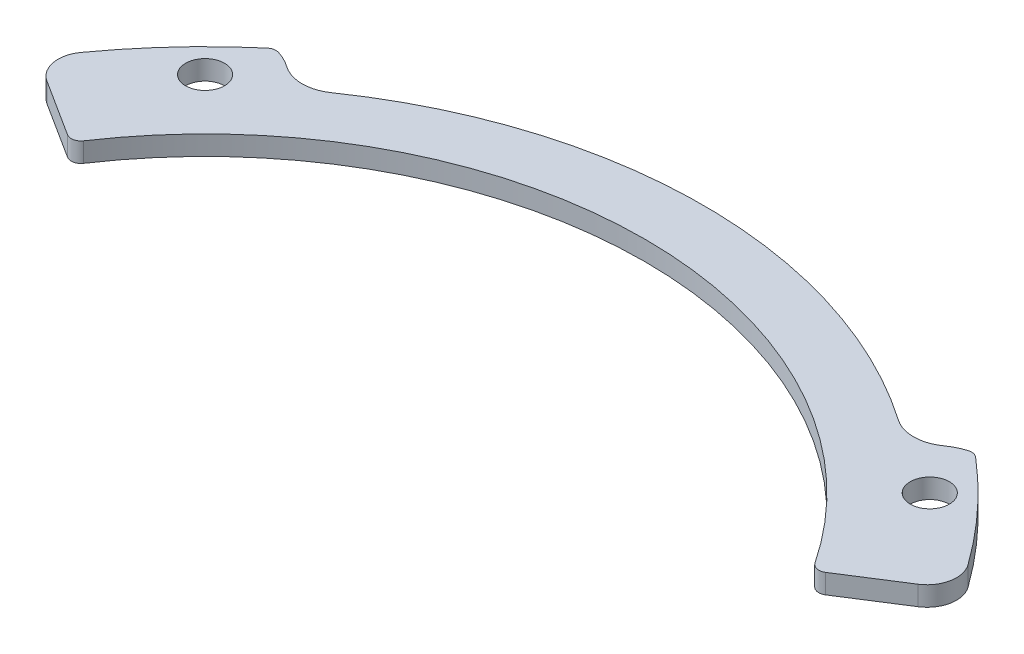
SolidWorks part; units mm, degrees
material "Thornel Mat VMA"
ref_plane "前视基准面" through (0, 0, 0) normal (0, 0, 1) x (1, 0, 0)
ref_plane "上视基准面" through (0, 0, 0) normal (0, 1, 0) x (1, 0, 0)
ref_plane "右视基准面" through (0, 0, 0) normal (1, 0, 0) x (0, 0, -1)
sketch "草图1" plane through (0, 0, 0) normal (0, 1, 0) x (1, 0, 0)
  line L1 (0, -1.1) -> (0, 1.1) construction
  line L2 (-37.9948, 24.2053) -> (-44.6281, 28.4312)
  line L3 (37.9948, 24.2053) -> (44.6281, 28.4312)
  arc A0 (37.9948, 24.2053) -> (-37.9948, 24.2053) centre (0, 0) ccw
  circle A3 centre (0, 52.5) radius 2 construction
  circle A4 centre (0, 0) radius 52.5 construction
  circle A6 centre (37.1231, 37.1231) radius 2
  circle A8 centre (52.5, 0) radius 2 construction
  circle A10 centre (37.1231, -37.1231) radius 2 construction
  circle A12 centre (0, 0) radius 49 construction
  arc A13 (45.4511, 32.7139) -> (-45.4511, 32.7139) centre (0, 0) ccw
  circle A14 centre (0, -52.5) radius 2 construction
  circle A15 centre (-37.1231, -37.1231) radius 2 construction
  circle A16 centre (-52.5, 0) radius 2 construction
  circle A17 centre (-37.1231, 37.1231) radius 2
  arc A18 (-44.6281, 28.4312) -> (-45.4511, 32.7139) centre (-43.0162, 30.9614) cw
  arc A19 (44.6281, 28.4312) -> (45.4511, 32.7139) centre (43.0162, 30.9614) ccw
  dimension "D1" = 90.1
  dimension "D2" = 98
  dimension "D3" = 105
  dimension "D4" = 4
  dimension "D5" = 56
  dimension "D6" = 3
  dimension "D8" = 115
  dimension "D7" = 8
extrude "凸台-拉伸1" add sketch "草图1" along normal blind 2
sketch "草图2" plane through (0, 2, 0) normal (0, 1, 0) x (1, 0, 0)
  line L6 (-1.1, 0) -> (1.1, 0) construction
  line L7 (0, -1.1) -> (0, 1.1) construction
  arc A5 (45.4511, 32.7139) -> (-45.4511, 32.7139) centre (0, 0) ccw construction
  arc A72 (-29.0476, 41.9803) -> (29.0476, 41.9803) centre (0, 0) cw
  arc A73 (-33.6434, 42.011) -> (-35.8826, 42.9935) centre (-37.1231, 37.1231) ccw
  circle A74 centre (0, 0) radius 45.05 construction
  arc A75 (45.4511, 32.7139) -> (-45.4511, 32.7139) centre (0, 0) ccw construction
  arc A76 (35.8826, 42.9935) -> (-35.8826, 42.9935) centre (0, 0) ccw
  arc A77 (33.6434, 42.011) -> (35.8826, 42.9935) centre (37.1231, 37.1231) cw
  arc A82 (-29.0476, 41.9803) -> (-33.6434, 42.011) centre (-31.3236, 45.2696) cw
  arc A83 (29.0476, 41.9803) -> (33.6434, 42.011) centre (31.3236, 45.2696) ccw
  circle A84 centre (-37.1231, 37.1231) radius 2 construction
  dimension "D5" = 6
  dimension "D6" = 6
  dimension "D7" = 4
extrude "切除-拉伸1" cut sketch "草图2" against normal through all
chamfer "倒角1" [suppressed] distance 2 distance2 1.3
fillet "圆角1" radius 1 4 edges at (35.8826, 1, -42.9935) (-35.8826, 1, -42.9935) (37.9948, 1, -24.2053) (-37.9948, 1, -24.2053)
